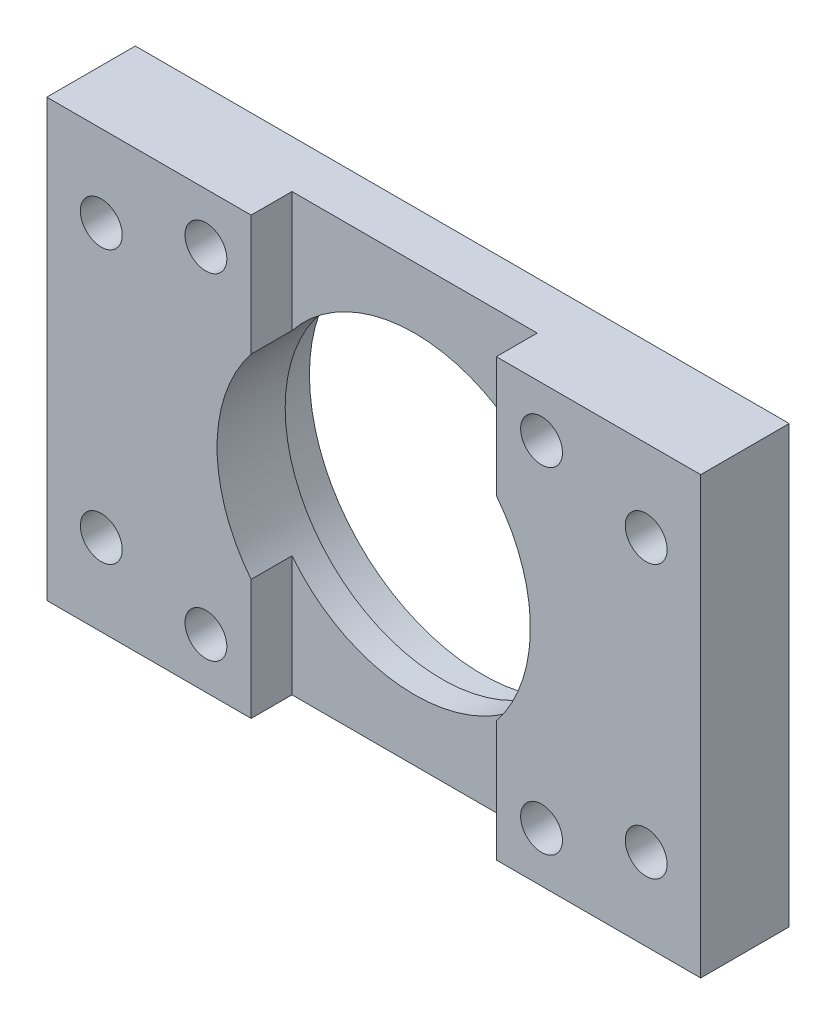
SolidWorks part; units mm, degrees
ref_plane "Front Plane" through (0, 0, 0) normal (0, 0, 1) x (1, 0, 0)
ref_plane "Top Plane" through (0, 0, 0) normal (0, 1, 0) x (1, 0, 0)
ref_plane "Right Plane" through (0, 0, 0) normal (1, 0, 0) x (0, 0, -1)
sketch "Sketch1" plane through (0, 0, 0) normal (0, 0, 1) x (1, 0, 0)
  line L1 (19.05, 12.7) -> (-19.05, 12.7)
  line L2 (19.05, 12.7) -> (19.05, -12.7)
  line L3 (19.05, -12.7) -> (-19.05, -12.7)
  line L4 (-19.05, 12.7) -> (-19.05, -12.7)
  line L5 (19.05, 12.7) -> (-19.05, -12.7) construction
  line L6 (19.05, -12.7) -> (-19.05, 12.7) construction
  point P1 (0, 0)
  dimension "D2" = 25.4
  dimension "D3" = 38.1
extrude "Boss-Extrude1" add sketch "Sketch1" along normal blind 6.35
sketch "Sketch6" plane through (0, 0, 6.35) normal (0, 0, 1) x (1, 0, 0)
  circle A0 centre (0, 0) radius 9.1281
  dimension "D1" = 18.2562
extrude "Cut-Extrude1" cut sketch "Sketch6" against normal through all
sketch "Sketch8" plane through (0, 0, 6.35) normal (0, 0, 1) x (1, 0, 0)
  line L0 (19.05, 12.7) -> (-19.05, 12.7) construction
  line L1 (-7.1438, -12.7) -> (7.1437, -12.7)
  line L2 (-7.1438, -12.7) -> (-7.1438, 12.7)
  line L3 (-7.1438, 12.7) -> (7.1437, 12.7)
  line L4 (7.1437, -12.7) -> (7.1437, 12.7)
  line L5 (-7.1438, -12.7) -> (7.1437, 12.7) construction
  line L6 (-7.1438, 12.7) -> (7.1437, -12.7) construction
  point P0 (0, 0)
  dimension "D1" = 14.2875
extrude "Cut-Extrude2" cut sketch "Sketch8" against normal offset from surface (2.3812 mm away) 3.9688 up to face at (9.1281, 0, 0)
sketch "Sketch14" plane through (0, 0, 0) normal (0, 0, -1) x (-1, 0, 0)
  line L1 (-19.05, 12.7) -> (19.05, 12.7)
  line L2 (-19.05, 12.7) -> (-19.05, -12.7)
  line L3 (-19.05, -12.7) -> (19.05, -12.7)
  line L4 (19.05, 12.7) -> (19.05, -12.7)
  line L5 (-19.05, 12.7) -> (19.05, -12.7) construction
  line L6 (-19.05, -12.7) -> (19.05, 12.7) construction
  circle A0 centre (0, 0) radius 11.3665
  line M12 (19.05, -12.7) -> (19.05, 12.7)
  line M13 (19.05, 12.7) -> (-19.05, 12.7)
  line M14 (-19.05, 12.7) -> (-19.05, -12.7)
  line M15 (-19.05, -12.7) -> (19.05, -12.7)
  dimension "D1" = 22.733
extrude "Cut-Extrude3" cut sketch "Sketch14" against normal blind 1.1906 contours A0 M15 M12 M13 M14
sketch "Sketch19" plane through (0, 0, 0) normal (0, 0, -1) x (-1, 0, 0)
  circle A0 centre (0, 0) radius 10.0965
  dimension "D1" = 20.193
extrude "Cut-Extrude4" cut sketch "Sketch19" against normal blind 2.3813
hole_wizard "#2 Clearance Hole1" positions "Sketch15" profile "Sketch16" hole size "#2" standard "ANSI Inch" end condition through all
sketch "Sketch15" plane through (0, 0, 1.1906) normal (0, 0, -1) x (-1, 0, 0)
  line L0 (0, 12.5458) -> (0, -12.2015) construction
  line L1 (-13.6002, 0) -> (15.1927, 0) construction
  point P0 (-9.779, 9.779)
  point P2 (9.779, 9.779)
  point P4 (9.779, -9.779)
  point P6 (-9.779, -9.779)
  dimension "D1" = 19.558
  dimension "D2" = 19.558
sketch "Sketch16" plane through (9.779, 9.779, 1.1906) normal (1, 0, 0) x (0, 1, 0)
  line L0 (0, 0) -> (0, 5.1594)
  line L1 (0, 5.1594) -> (1.2192, 5.1594)
  line L2 (1.2192, 5.1594) -> (1.2192, 0)
  line L5 (1.2192, 0) -> (0, 0)
  line L11 (0, -6.35) -> (0, 107.95) construction
  dimension "Thru Hole Dia." = 2.4384
  dimension "Thru Hole Depth" = 5.1594
hole_wizard "CBORE for #2 Pan Head Machine Screw1" positions "Sketch17" profile "Sketch18" counterbore size "#2" standard "ANSI Inch" end condition through all
sketch "Sketch17" plane through (0, 0, 1.1906) normal (0, 0, -1) x (-1, 0, 0)
  line L0 (0, 8.0267) -> (0, -8.7584) construction
  line L1 (-14.3749, 0) -> (16.6129, 0) construction
  point P0 (-15.875, 7.9375)
  point P2 (-15.875, -7.9375)
  point P4 (15.875, -7.9375)
  point P6 (15.875, 7.9375)
  dimension "D1" = 31.75
  dimension "D2" = 15.875
sketch "Sketch18" plane through (15.875, 7.9375, 1.1906) normal (1, 0, 0) x (0, 1, 0)
  line L0 (0, 0) -> (0, 5.1594)
  line L1 (0, 5.1594) -> (1.2192, 5.1594)
  line L3 (1.2192, 5.1594) -> (1.2192, 2.3812)
  line L4 (1.2192, 2.3812) -> (2.3812, 2.3812)
  line L5 (2.3812, 2.3812) -> (2.3812, 0)
  line L7 (2.3812, 0) -> (0, 0)
  line L11 (0, -6.35) -> (0, 107.95) construction
  dimension "Thru Hole Dia." = 2.4384
  dimension "Thru Hole Depth" = 5.1594
  dimension "C'Bore Dia." = 4.7625
  dimension "C'Bore Depth" = 2.3812
